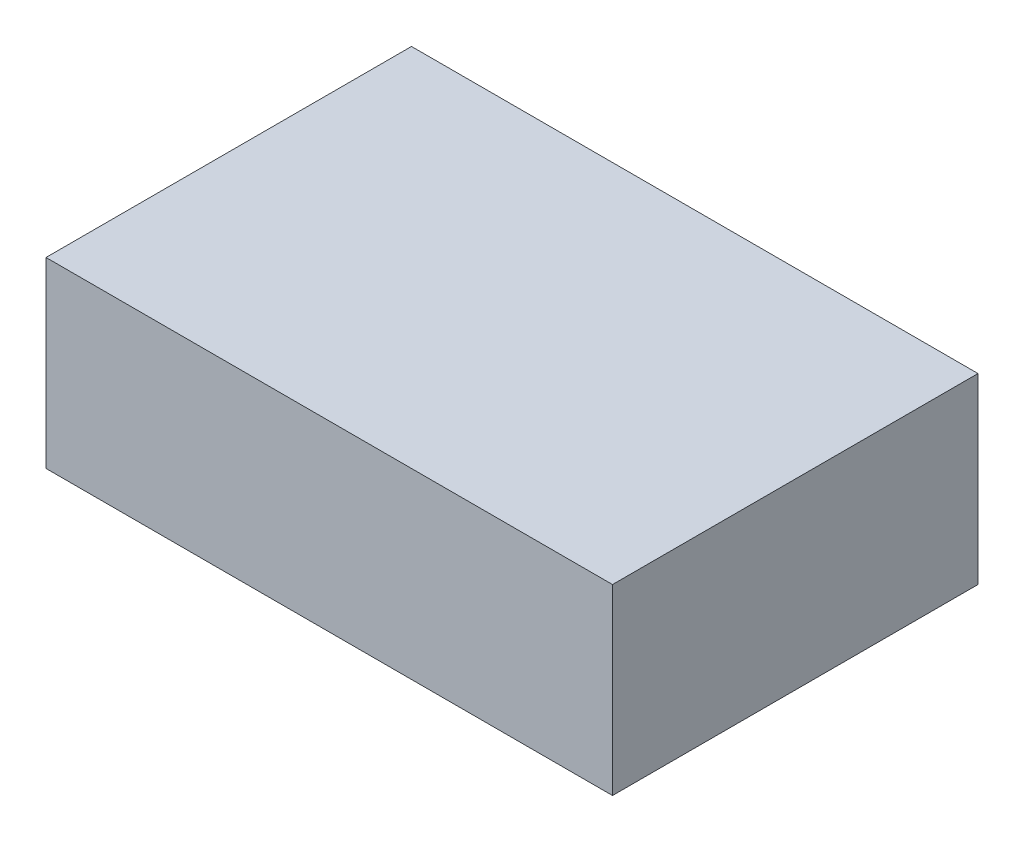
SolidWorks part; units mm, degrees
ref_plane "Front Plane" through (0, 0, 0) normal (0, 0, 1) x (1, 0, 0)
ref_plane "Top Plane" through (0, 0, 0) normal (0, 1, 0) x (1, 0, 0)
ref_plane "Right Plane" through (0, 0, 0) normal (1, 0, 0) x (0, 0, -1)
sketch "Sketch1" plane through (0, 0, 0) normal (0, 1, 0) x (1, 0, 0)
  line L1 (0, 0) -> (31, 0)
  line L2 (0, 0) -> (0, 20)
  line L3 (0, 20) -> (31, 20)
  line L4 (31, 0) -> (31, 20)
extrude "Boss-Extrude1" add sketch "Sketch1" against normal blind 10
